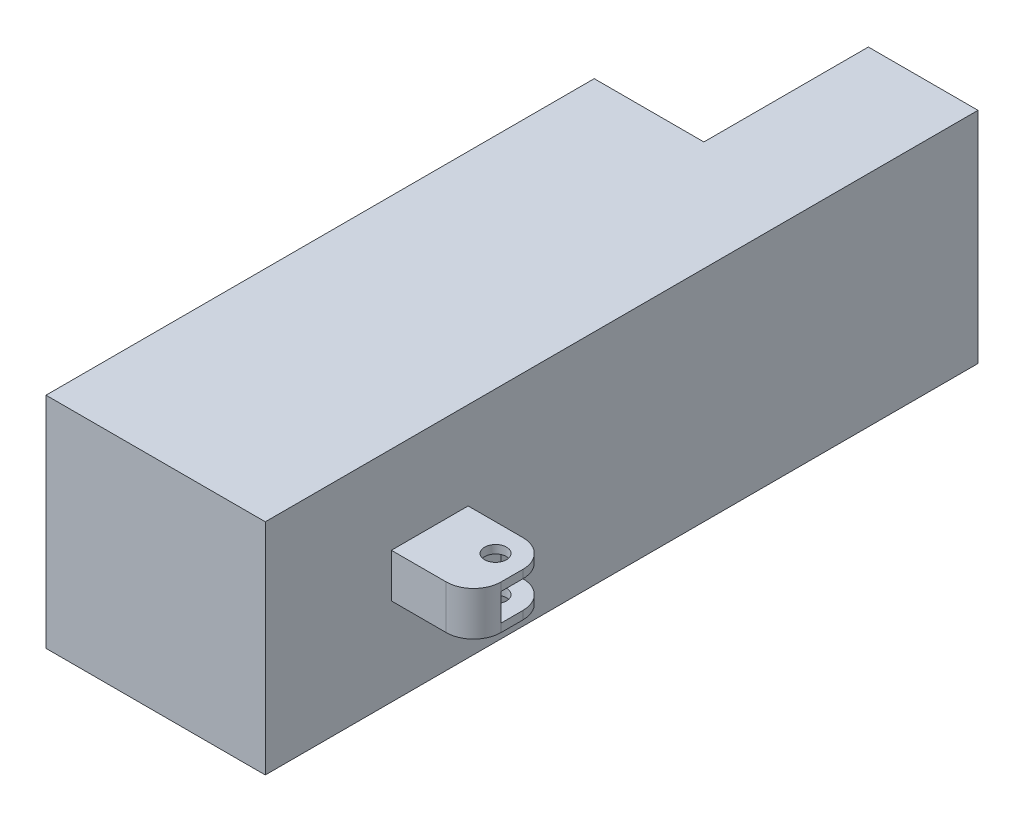
SolidWorks part; units mm, degrees
ref_plane "Front Plane" through (0, 0, 0) normal (0, 0, 1) x (1, 0, 0)
ref_plane "Top Plane" through (0, 0, 0) normal (0, 1, 0) x (1, 0, 0)
ref_plane "Right Plane" through (0, 0, 0) normal (1, 0, 0) x (0, 0, -1)
sketch "Sketch1" plane through (0, 0, 0) normal (0, 1, 0) x (1, 0, 0)
  line L1 (0, 0) -> (-200, 0)
  line L2 (0, 0) -> (0, 500)
  line L3 (0, 500) -> (-200, 500)
  line L4 (-200, 0) -> (-200, 500)
  dimension "D1" = 200
  dimension "D2" = 500
extrude "Boss-Extrude1" add sketch "Sketch1" along normal blind 200
sketch "Sketch2" plane through (0, 0, 0) normal (1, 0, 0) x (0, 0, -1)
  line L0 (13.8943, 100) -> (515.7565, 100) construction
  line L2 (0, 200) -> (0, 0) construction
  line L3 (115, 80) -> (185, 80)
  line L4 (115, 80) -> (115, 120)
  line L5 (115, 120) -> (185, 120)
  line L6 (185, 80) -> (185, 120)
  line L7 (115, 80) -> (185, 120) construction
  line L8 (115, 120) -> (185, 80) construction
  line L9 (0, 200) -> (500, 200) construction
  point P1 (150, 100)
  dimension "D1" = 70
  dimension "D2" = 40
  dimension "D3" = 150
  dimension "D4" = 100
extrude "Boss-Extrude2" add sketch "Sketch2" along normal blind 75
fillet "Fillet1" radius 25 2 edges at (75, 100, -115) (75, 100, -185)
sketch "Sketch3" plane through (0, 120, 0) normal (0, 1, 0) x (1, 0, 0)
  circle A0 centre (50, 160) radius 10
  dimension "D1" = 20
extrude "Cut-Extrude1" cut sketch "Sketch3" against normal blind 75
sketch "Sketch4" plane through (0, 0, -500) normal (0, 0, -1) x (-1, 0, 0)
  line L0 (0, 0) -> (200, 0) construction
  line L1 (0, 200) -> (100, 200)
  line L2 (0, 200) -> (0, 0)
  line L3 (0, 0) -> (100, 0)
  line L4 (100, 200) -> (100, 0)
  dimension "D1" = 100
extrude "Boss-Extrude3" add sketch "Sketch4" along normal blind 150
ref_plane "Plane1" through (0, 80, -115) normal (0, -1, 0) x (-1, 0, 0)
sketch "Sketch6" plane through (75, 0, 0) normal (1, 0, 0) x (0, 0, -1)
  line L0 (140, 120) -> (140, 80) construction
  line L1 (140, 112.5) -> (185, 112.5)
  line L2 (140, 112.5) -> (140, 87.5)
  line L3 (140, 87.5) -> (185, 87.5)
  line L4 (185, 112.5) -> (185, 87.5)
  line L5 (185, 80) -> (185, 120) construction
  line L6 (160, 80) -> (185, 80) construction
  dimension "D1" = 25
  dimension "D2" = 7.5
extrude "Cut-Extrude2" cut sketch "Sketch6" against normal blind 45
fillet "Fillet2" radius 15 1 edges at (30, 100, -140)
